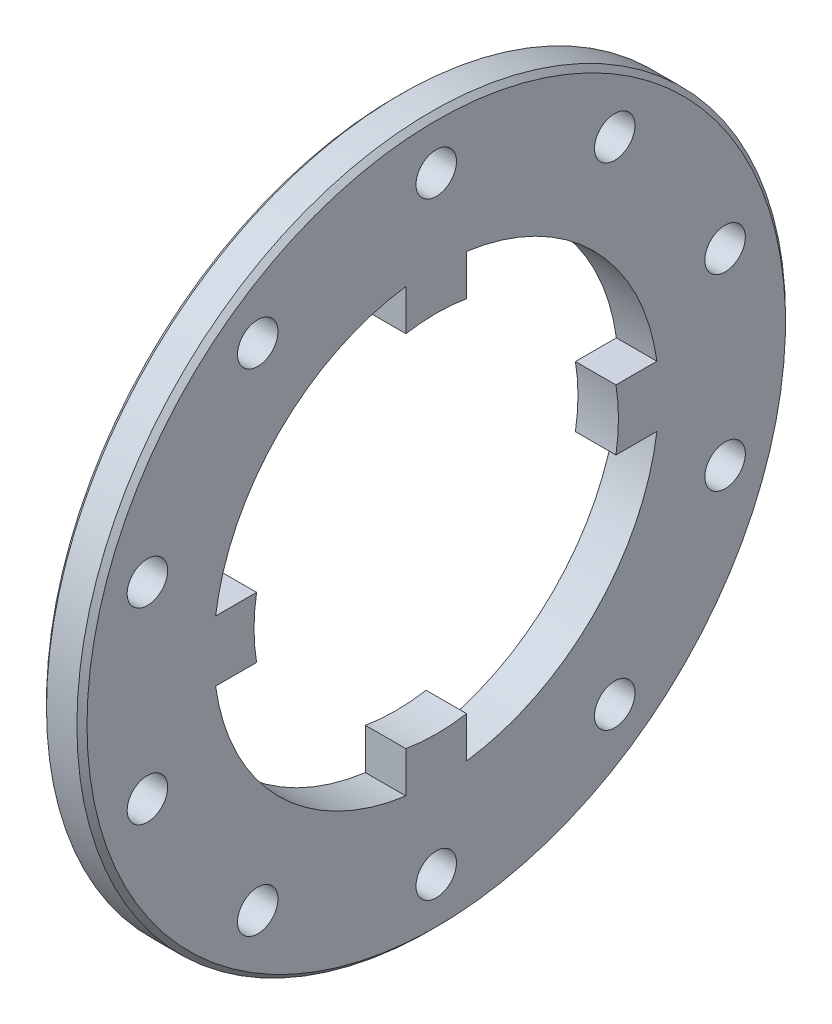
SolidWorks part; units mm, degrees
ref_plane "Plan1" through (0, 0, 0) normal (0, 0, 1) x (1, 0, 0)
ref_plane "Plan2" through (0, 0, 0) normal (0, 1, 0) x (1, 0, 0)
ref_plane "Plan3" through (0, 0, 0) normal (1, 0, 0) x (0, 0, -1)
sketch "Esquisse1" plane through (0, 0, 0) normal (0, 0, 1) x (1, 0, 0)
  line L0 (0, 35) -> (0, 18)
  line L1 (0, 18) -> (4, 18)
  line L2 (4, 18) -> (4, 35)
  line L5 (4, 35) -> (0, 35)
  line L6 (0, 0) -> (55, 0) construction
  dimension "D1" = 35
  dimension "D3" = 4
  dimension "D4" = 18
revolve "Base-Révolution" add sketch "Esquisse1" angle 360 about L6
sketch "Esquisse2" plane through (0, 0, 0) normal (-1, 0, 0) x (0, 0, 1)
  line L0 (-3, 16) -> (-3, 21.7945)
  line L1 (3, 16) -> (3, 21.7945)
  line L2 (-3, 16) -> (3, 16)
  line L3 (16, 3) -> (21.7945, 3)
  line L4 (16, -3) -> (21.7945, -3)
  line L5 (16, 3) -> (16, -3)
  line L6 (3, -16) -> (3, -21.7945)
  line L7 (-3, -16) -> (-3, -21.7945)
  line L8 (3, -16) -> (-3, -16)
  line L9 (-16, -3) -> (-21.7945, -3)
  line L10 (-16, 3) -> (-21.7945, 3)
  line L11 (-16, -3) -> (-16, 3)
  arc A0 (-3, 21.7945) -> (-21.7945, 3) centre (0, 0) ccw
  arc A1 (21.7945, 3) -> (3, 21.7945) centre (0, 0) ccw
  arc A2 (3, -21.7945) -> (21.7945, -3) centre (0, 0) ccw
  arc A3 (-21.7945, -3) -> (-3, -21.7945) centre (0, 0) ccw
  dimension "D2" = 44
  dimension "D1" = 6
  dimension "D3" = 3
  dimension "D4" = 16
extrude "Enlèv. mat.-Extru.1" cut sketch "Esquisse2" against normal through all
chamfer "Chanfrein1" distance 0.5 angle 45
sketch "Esquisse3" plane through (0, 0, 0) normal (-1, 0, 0) x (0, 0, 1)
  circle A0 centre (0, 30) radius 2
  circle A3 centre (17.6336, 24.2705) radius 2
  circle A4 centre (28.5317, 9.2705) radius 2
  circle A5 centre (28.5317, -9.2705) radius 2
  circle A6 centre (17.6336, -24.2705) radius 2
  circle A7 centre (0, -30) radius 2
  circle A9 centre (-17.6336, -24.2705) radius 2
  circle A10 centre (-28.5317, -9.2705) radius 2
  circle A11 centre (-28.5317, 9.2705) radius 2
  circle A12 centre (-17.6336, 24.2705) radius 2
  dimension "D1" = 4
  dimension "D2" = 30
extrude "Enlèv. mat.-Extru.2" cut sketch "Esquisse3" against normal through all
